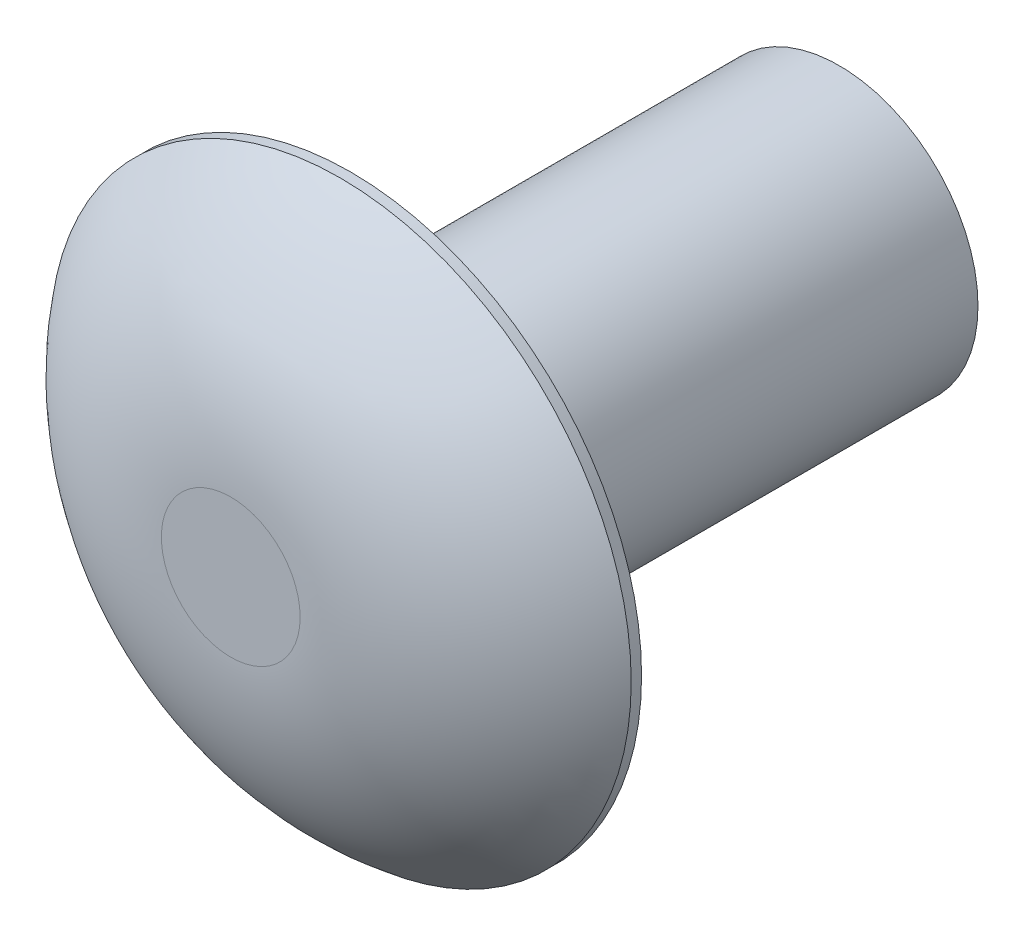
SolidWorks part; units mm, degrees
ref_plane "Front" through (0, 0, 0) normal (0, 0, 1) x (1, 0, 0)
ref_plane "Top" through (0, 0, 0) normal (0, 1, 0) x (1, 0, 0)
ref_plane "Right" through (0, 0, 0) normal (1, 0, 0) x (0, 0, -1)
sketch "layout" plane through (0, 0, 0) normal (1, 0, 0) x (0, 0, -1)
  line L0 (-18.8214, 0) -> (-2.0574, 0) construction
  line L1 (-2.0574, 0) -> (0, 0) construction
  line L2 (0, 0) -> (8.382, 0) construction
  line L3 (8.382, 0) -> (10.4394, 0) construction
  line L8 (0, 4.9911) -> (0, -4.9911) construction
  line L9 (8.382, 2.3813) -> (8.382, -2.3813) construction
  point P7 (-2.0574, 4.9911)
  point P10 (0, 4.9911)
  point P17 (0, -4.9911)
  point P18 (8.382, 2.3813)
  point P19 (-18.8214, 0)
  point P21 (8.382, -2.3813)
  dimension "D5" = 2.0574
sketch "Sketch2" plane through (0, 0, 0) normal (1, 0, 0) x (0, 0, -1)
  line L0 (-18.8214, 0) -> (-18.8214, 1.1906)
  line L1 (-18.8214, 1.1906) -> (0, 1.1906) construction
  line L2 (0, 4.9911) -> (0, -4.9911) construction
  line L3 (0, 0) -> (0, 4.9911) construction
  line L4 (-2.0574, 0) -> (-2.0574, -1.8472) construction
  line L5 (8.382, 2.3813) -> (0, 2.3813)
  line L6 (8.382, 2.3813) -> (8.382, 0) construction
  line L7 (8.8963, 2.3813) -> (8.8963, -2.3813) construction
  line L8 (7.3533, 0) -> (8.382, 0) construction
  line L9 (10.4394, 0) -> (10.4394, 2.3813) construction
  line L10 (8.382, 2.3813) -> (8.8963, 2.3813) construction
  line L11 (8.8963, 2.3813) -> (9.4107, 2.3813) construction
  line L12 (-18.8214, 0) -> (8.382, 0)
  line L13 (-2.0574, 1.1906) -> (-2.0574, 0) construction
  line L14 (9.4107, 2.3813) -> (9.9251, 2.3813) construction
  line L15 (9.9251, 2.3813) -> (10.4394, 2.3813) construction
  line L16 (8.382, 2.2451) -> (8.382, 2.3813)
  line L17 (8.382, 2.2451) -> (8.382, 0)
  line L19 (0, 2.3813) -> (0, 4.9911)
  line L20 (-2.0574, 1.1906) -> (-18.8214, 1.1906)
  line L22 (0, 4.9911) -> (-0.1778, 4.9911)
  arc A2 (-0.1778, 4.9911) -> (-2.0574, 1.1906) centre (2.7246, 1.1906) ccw
  ellipse E0 centre (8.8963, 0) end of major axis (8.8963, -2.3813) minor radius 1.5431 (10.4394, 0) -> (8.382, 2.2451) ccw construction
  point P20 (8.382, 1.1906)
  dimension "D1" = 0.1778
revolve "Revolve1" add sketch "Sketch2" angle 360 about L12
sketch "Sketch3" plane through (0, 0, 0) normal (0, 1, 0) x (1, 0, 0)
  line L0 (0, -18.8214) -> (1.3938, -17.0049)
  line L1 (-1.1906, -18.8214) -> (1.1906, -18.8214) construction
  line L3 (0, -18.8214) -> (0, -19.3294) construction
  line L4 (0, -18.8214) -> (-1.3938, -17.0049)
  line L5 (-1.3938, -17.0049) -> (-1.3938, -19.3294)
  line L6 (-1.3938, -19.3294) -> (1.3938, -19.3294)
  line L7 (1.3938, -19.3294) -> (1.3938, -17.0049)
  dimension "D1" = 75
  dimension "D2" = 0.2032
  dimension "D3" = 0.508
extrude "Cut-Extrude1" cut sketch "Sketch3" against normal through all both and the other way through all
sketch "Sketch5" plane through (0, 0, 0) normal (1, 0, 0) x (0, 0, -1)
  line L0 (-18.8214, 0) -> (-17.2697, 1.5081)
  line L1 (-18.8214, -1.1906) -> (-18.8214, 1.1906) construction
  line L2 (-17.2697, 1.5081) -> (-19.1389, 1.5081)
  line L3 (-19.1389, 1.5081) -> (-19.1389, -1.5081)
  line L4 (-19.1389, -1.5081) -> (-17.2697, -1.5081)
  line L5 (-17.2697, -1.5081) -> (-18.8214, 0)
  line L6 (-18.8214, 0) -> (-9.2614, 0) construction
  line L7 (-2.0574, 1.1906) -> (-18.8214, 1.1906) construction
  line L8 (-17.2697, 0) -> (-17.2697, 1.5081) construction
  ellipse E0 centre (-18.8214, 0) end of major axis (-20.3731, 0) minor radius 1.1906 (-18.8214, -1.1906) -> (-18.8214, 1.1906) ccw construction
  dimension "D1" = 0.3175
  dimension "D2" = 0.3175
extrude "Cut-Extrude2" cut sketch "Sketch5" against normal through all both and the other way through all
fillet "Fillet2" radius 0.254 1 edges at (2.3813, 0, 0)
sketch "Sketch6" plane through (0, 0, 0) normal (1, 0, 0) x (0, 0, -1)
  line L0 (-6.4008, 1.1906) -> (-6.2484, 1.1906)
  line L1 (-18.8214, 0) -> (-2.0574, 0) construction
  line L2 (-6.2484, 1.1906) -> (-6.2484, -1.1906) construction
  line L3 (-2.0574, 1.1906) -> (-2.0574, -1.1906) construction
  line L4 (-17.5964, -1.1906) -> (-2.0574, -1.1906) construction
  arc A0 (-6.4008, 1.1906) -> (-6.2484, 1.1906) centre (-6.3246, 1.1906) ccw
  point P11 (-6.2484, 0)
  dimension "D2" = 0.0762
  dimension "D1" = 12.573
  dimension "D3" = 16.764
revolve "Cut-Revolve1" [suppressed] cut sketch "Sketch6" angle 360 about L1
pattern_linear "LPattern1" [suppressed] count 18 spacing 0.762 along (0, 0, -1)
sketch "Sketch7" plane through (0, 0, 0) normal (0, 1, 0) x (1, 0, 0)
  line L0 (1.1906, -2.0574) -> (-1.1906, -2.0574) construction
  line L1 (-1.1906, -2.0574) -> (1.1906, -2.0574)
  line L2 (-1.1906, -2.0574) -> (-1.1906, -19.7976)
  line L3 (-1.1906, -19.7976) -> (1.1906, -19.7976)
  line L4 (1.1906, -2.0574) -> (1.1906, -19.7976)
extrude "Cut-Extrude3" cut sketch "Sketch7" against normal through all both and the other way through all
equation "\"D5@layout\"=\"Head Height@layout\"*1"
equation "\"D9@layout\"=\"length@layout\"*2"
equation "\"D2@Sketch5\"=\"D1@Sketch5\""
equation "\"D1@Sketch6\"=\"D3@Sketch6\"*.75"
